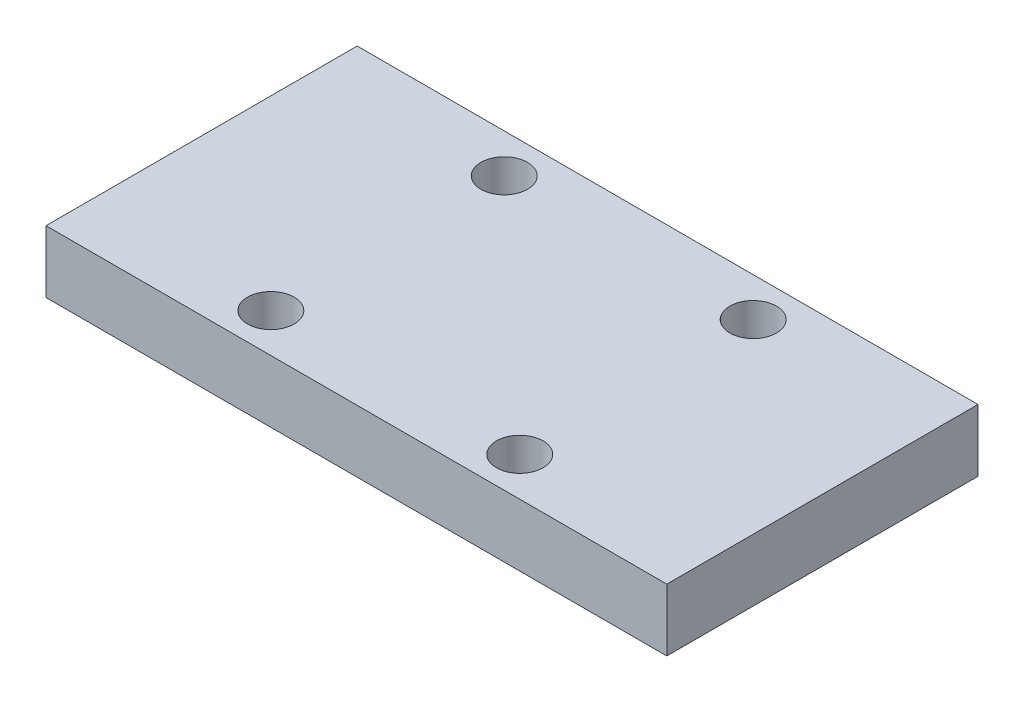
SolidWorks part; units mm, degrees
material "聚脂树脂"
ref_plane "前视基准面" through (0, 0, 0) normal (0, 0, 1) x (1, 0, 0)
ref_plane "上视基准面" through (0, 0, 0) normal (0, 1, 0) x (1, 0, 0)
ref_plane "右视基准面" through (0, 0, 0) normal (1, 0, 0) x (0, 0, -1)
other "Configuration Table"
sketch "草图1" plane through (0, 0, 0) normal (0, 1, 0) x (1, 0, 0)
  line L0 (0, 0) -> (26.53, 0) construction
  line L1 (-19.95, -10) -> (19.95, -10)
  line L2 (-19.95, -10) -> (-19.95, 10)
  line L3 (-19.95, 10) -> (19.95, 10)
  line L4 (19.95, -10) -> (19.95, 10)
  line L5 (-19.95, -10) -> (19.95, 10) construction
  line L6 (-19.95, 10) -> (19.95, -10) construction
  line L7 (0, 0) -> (0, 15.2425) construction
  circle A0 centre (8, 7.5) radius 1.5
  circle A1 centre (8, -7.5) radius 1.5
  circle A2 centre (-8, -7.5) radius 1.5
  circle A3 centre (-8, 7.5) radius 1.5
  point P0 (0, 0)
  dimension "D3" = 3
  dimension "D4" = 16
  dimension "D5" = 15
  dimension "D1" = 39.9
  dimension "D2" = 20
extrude "凸台-拉伸1" add sketch "草图1" along normal blind 4
